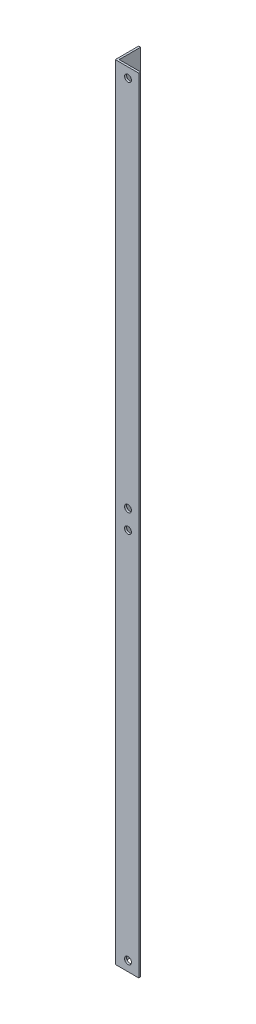
SolidWorks part; units mm, degrees
material "Galvanized Steel"
ref_plane "Front Plane" through (0, 0, 0) normal (0, 0, 1) x (1, 0, 0)
ref_plane "Top Plane" through (0, 0, 0) normal (0, 1, 0) x (1, 0, 0)
ref_plane "Right Plane" through (0, 0, 0) normal (1, 0, 0) x (0, 0, -1)
sketch "Sketch18" plane through (0, 0, 0) normal (0, 1, 0) x (1, 0, 0)
  line L0 (3.175, 38.1) -> (3.175, 3.175)
  line L1 (0, 0) -> (38.1, 0)
  line L2 (0, 0) -> (0, 38.1)
  line L3 (0, 38.1) -> (3.175, 38.1)
  line L4 (38.1, 0) -> (38.1, 3.175)
  line L5 (3.175, 3.175) -> (38.1, 3.175)
  dimension "D1" = 38.1
  dimension "D2" = 3.175
extrude "Boss-Extrude1" add sketch "Sketch18" along normal mid plane 1270
sketch "Sketch19" plane through (0, 0, -3.175) normal (0, 0, -1) x (-1, 0, 0)
  line L0 (-38.1, 635) -> (-3.175, 635) construction
  circle A0 centre (-20.6375, 619.125) radius 5.588
  circle A1 centre (-20.6375, 15.24) radius 5.588
  point P4 (-20.6375, 635)
  point P7 (0, 0)
  point P8 (-20.6375, 1183.4405)
  dimension "D1" = 11.176
  dimension "D2" = 15.875
  dimension "D3" = 619.76
extrude "Cut-Extrude2" cut sketch "Sketch19" against normal through all
mirror "Mirror2" about plane through (0, 0, 0) normal (0, 1, 0) of "Cut-Extrude2"
